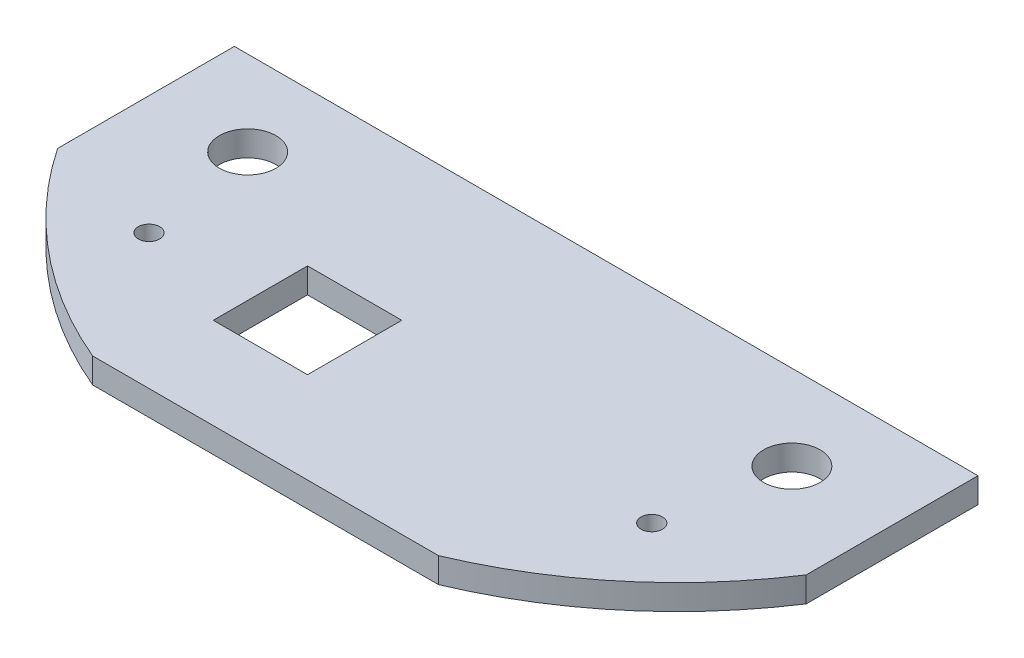
SolidWorks part; units mm, degrees
ref_plane "Plan de face" through (0, 0, 0) normal (0, 0, 1) x (1, 0, 0)
ref_plane "Plan de dessus" through (0, 0, 0) normal (0, 1, 0) x (1, 0, 0)
ref_plane "Plan de droite" through (0, 0, 0) normal (1, 0, 0) x (0, 0, -1)
sketch "Esquisse1" plane through (0, 0, 0) normal (0, 1, 0) x (1, 0, 0)
  line L0 (-58.9016, 6.7115) -> (-58.9016, 32.4862)
  line L1 (31.5, 12.5) -> (-31.5, 12.5)
  line L2 (31.5, 12.5) -> (31.5, -12.5)
  line L3 (31.5, -12.5) -> (-31.5, -12.5)
  line L4 (-31.5, 12.5) -> (-31.5, -12.5)
  line L5 (31.5, 12.5) -> (-31.5, -12.5) construction
  line L6 (31.5, -12.5) -> (-31.5, 12.5) construction
  line L7 (-58.9016, 32.4862) -> (59.4279, 32.4862)
  line L8 (59.4279, 32.4862) -> (59.4279, 7.4872)
  line L9 (0, 0) -> (0, 47.2436) construction
  line L10 (-58.9016, 6.7115) -> (0, 47.2436) construction
  line L11 (0, 47.2436) -> (59.4279, 7.4872) construction
  line L12 (-43.3, 22.2414) -> (43.3, 22.2414) construction
  line L13 (43.3, 22.2414) -> (0, 47.2436) construction
  line L14 (0, 47.2436) -> (-43.3, 22.2414) construction
  line L15 (-58.9016, 6.7115) -> (-58.9016, -21.4508)
  line L16 (-58.9016, -21.4508) -> (59.4279, -21.4508)
  line L17 (59.4279, -21.4508) -> (59.4279, 7.4872)
  point P8 (43.3, 22.2414)
  point P13 (0, 47.2436)
  point P14 (-43.3, 22.2414)
  point P16 (0, 22.2414)
  dimension "D3" = 71.5
  dimension "D1" = 25
  dimension "D2" = 63
  dimension "D4" = 50
  dimension "D5" = 86.6
extrude "Boss.-Extru.1" add sketch "Esquisse1" along normal blind 4
hole_wizard "Dégagement M81" positions "Esquisse2" profile "Esquisse4" hole size "M8" standard "DIN" end condition through all
sketch "Esquisse2" plane through (0, 4, 0) normal (0, 1, 0) x (1, 0, 0)
  line L0 (-43.3, 19) -> (0, 0) construction
  line L1 (0, 0) -> (43.3, 19) construction
  line L2 (43.3, 19) -> (-43.3, 19) construction
  point P0 (-43.3, 19)
  point P2 (43.3, 19)
  dimension "D1" = 86.6
  dimension "D2" = 19
sketch "Esquisse4" plane through (-43.3, 4, -19) normal (1, 0, 0) x (0, 0, 1)
  line L0 (0, 0) -> (0, 4)
  line L1 (0, 4) -> (4.5, 4)
  line L2 (4.5, 4) -> (4.5, 0)
  line L5 (4.5, 0) -> (0, 0)
  line L11 (0, -6.35) -> (0, 107.95) construction
  dimension "Diamètre du perçage jusqu'au prochain" = 9
  dimension "Profondeur du perçage jusqu'au prochain" = 4
sketch "Esquisse5" plane through (0, 4, 0) normal (0, 1, 0) x (1, 0, 0)
  line L0 (0, 44.0022) -> (0, 0) construction
  line L1 (-43.3, 19) -> (0, 44.0022) construction
  circle A0 centre (0, 44.0022) radius 71
  circle A1 centre (0, 44.0022) radius 96
  dimension "D1" = 25
  dimension "D3" = 142
  dimension "D2" = 50
extrude "Enlèv. mat.-Extru.1" cut sketch "Esquisse5" against normal through all
sketch "Esquisse6" plane through (0, 4, 0) normal (0, 1, 0) x (1, 0, 0)
  line L4 (31.5, -12.5) -> (31.5, 12.5) construction
  line L5 (-31.5, -12.5) -> (31.5, -12.5) construction
  line L6 (-31.5, 12.5) -> (-31.5, -12.5) construction
  line L7 (31.5, 12.5) -> (-31.5, 12.5) construction
  line L8 (31.5, -12.5) -> (31.5, 12.5)
  line L9 (-31.5, -12.5) -> (31.5, -12.5)
  line L10 (-31.5, 12.5) -> (-31.5, -12.5)
  line L11 (31.5, 12.5) -> (-31.5, 12.5)
extrude "Boss.-Extru.2" add sketch "Esquisse6" against normal up to surface (4 mm away) up to face at (-43.3, 0, -14.5)
sketch "Esquisse7" plane through (0, 4, 0) normal (0, 1, 0) x (1, 0, 0)
  line L1 (-22.8352, -6.9423) -> (-7.8352, -6.9423)
  line L2 (-22.8352, -6.9423) -> (-22.8352, 8.0577)
  line L3 (-22.8352, 8.0577) -> (-7.8352, 8.0577)
  line L4 (-7.8352, -6.9423) -> (-7.8352, 8.0577)
  line L5 (-22.8352, -6.9423) -> (-7.8352, 8.0577) construction
  line L6 (-22.8352, 8.0577) -> (-7.8352, -6.9423) construction
  point P0 (-15.3352, 0.5577)
  dimension "D1" = 15
extrude "Enlèv. mat.-Extru.2" cut sketch "Esquisse7" against normal through all
hole_wizard "Dégagement M31" positions "Esquisse8" profile "Esquisse9" hole size "M3" standard "DIN" end condition through all
sketch "Esquisse8" plane through (0, 4, 0) normal (0, 1, 0) x (1, 0, 0)
  point P0 (-40, 0)
  point P3 (40, 0)
sketch "Esquisse9" plane through (-40, 4, 0) normal (1, 0, 0) x (0, 0, 1)
  line L0 (0, 0) -> (0, 4)
  line L1 (0, 4) -> (1.7, 4)
  line L2 (1.7, 4) -> (1.7, 0)
  line L5 (1.7, 0) -> (0, 0)
  line L11 (0, -6.35) -> (0, 107.95) construction
  dimension "Diamètre du perçage jusqu'au prochain" = 3.4
  dimension "Profondeur du perçage jusqu'au prochain" = 4
